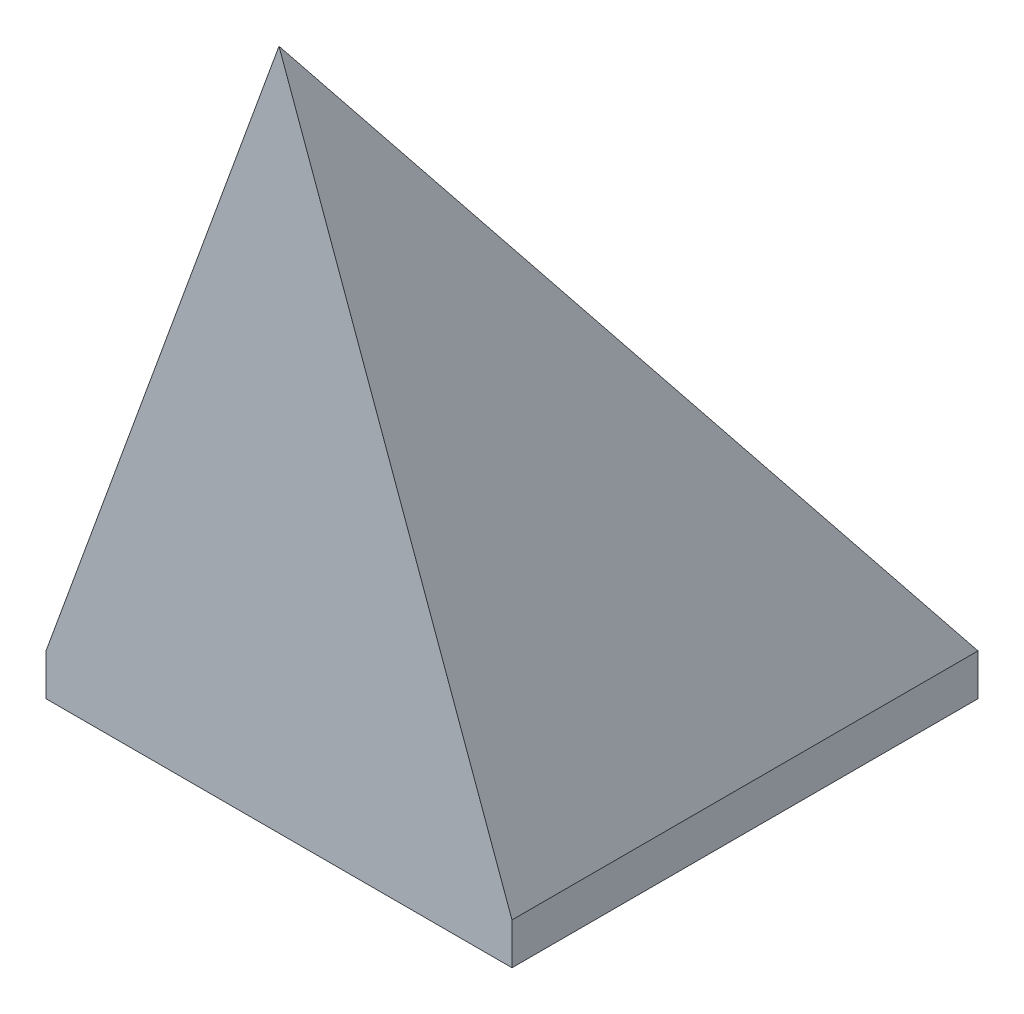
SolidWorks part; units mm, degrees
ref_plane "前视基准面" through (0, 0, 0) normal (0, 0, 1) x (1, 0, 0)
ref_plane "上视基准面" through (0, 0, 0) normal (0, 1, 0) x (1, 0, 0)
ref_plane "右视基准面" through (0, 0, 0) normal (1, 0, 0) x (0, 0, -1)
other "Configuration Table"
sketch "草图1" plane through (0, 0, 0) normal (0, 1, 0) x (1, 0, 0)
  line L1 (0, 0) -> (45, 0)
  line L2 (0, 0) -> (0, 45)
  line L3 (0, 45) -> (45, 45)
  line L4 (45, 0) -> (45, 45)
  circle A0 centre (15, 30) radius 1.7
  circle A1 centre (30, 30) radius 1.7
  circle A2 centre (15, 15) radius 1.7
  circle A3 centre (30, 15) radius 1.7
  point P15 (-39.4596, 30.7867)
  dimension "D3" = 3.4
  dimension "D4" = 3.4
  dimension "D5" = 3.4
  dimension "D6" = 3.4
  dimension "D1" = 45
  dimension "D2" = 45
  dimension "D7" = 15
  dimension "D8" = 15
  dimension "D9" = 15
  dimension "D10" = 15
  dimension "D11" = 15
  dimension "D12" = 15
  dimension "D13" = 15
  dimension "D14" = 15
extrude "凸台-拉伸1" add sketch "草图1" along normal blind 4
sketch "草图2" plane through (0, 0, 0) normal (0, 0, 1) x (1, 0, 0)
  line L0 (0, 4) -> (22.5, 65.8182)
  line L1 (22.5, 65.8182) -> (45, 4)
  line L2 (0, 4) -> (45, 4) construction
  line L3 (0, 4) -> (45, 4)
  dimension "D1" = 70
  dimension "D2" = 70
extrude "凸台-拉伸2" add sketch "草图2" against normal blind 5 contours L0 L1 L3
sketch "草图3" plane through (0, 4, 0) normal (0, 1, 0) x (1, 0, 0)
  line L0 (0, 5) -> (0, 45)
  line L1 (0, 45) -> (4, 45)
  line L2 (45, 45) -> (0, 45) construction
  line L3 (4, 45) -> (7, 5)
  line L4 (0, 5) -> (45, 5) construction
  line L5 (7, 5) -> (0, 5)
  dimension "D1" = 4
  dimension "D2" = 7
extrude "凸台-拉伸3" add sketch "草图3" along direction (0.342, 0.9397, 0) on the side of the normal up to vertex (61.8182 mm away)
sketch "草图4" plane through (0, 4, 0) normal (0, 1, 0) x (1, 0, 0)
  line L0 (45, 45) -> (41, 45)
  line L1 (45, 45) -> (4, 45) construction
  line L2 (41, 45) -> (38, 5)
  line L3 (7, 5) -> (45, 5) construction
  line L4 (38, 5) -> (45, 5)
  line L5 (45, 5) -> (45, 45)
  dimension "D1" = 4
  dimension "D2" = 7
extrude "凸台-拉伸4" add sketch "草图4" along direction (0.342, -0.9397, 0) on the side of the normal up to vertex (61.8182 mm away)
sketch "草图5" plane through (0, 0, 0) normal (0, 0, 1) x (1, 0, 0)
  line L0 (22.5, 65.8182) -> (19, 56.2021)
  line L1 (19, 56.2021) -> (11, 56.2021)
  line L2 (11, 56.2021) -> (11, 66.2021)
  line L3 (11, 66.2021) -> (34, 66.2021)
  line L4 (34, 66.2021) -> (34, 56.2021)
  line L5 (34, 56.2021) -> (26, 56.2021)
  line L6 (26, 56.2021) -> (22.5, 65.8182)
  dimension "D1" = 10
  dimension "D2" = 8
  dimension "D3" = 8
extrude "切除-拉伸1" cut sketch "草图5" against normal through all
sketch "草图6" plane through (41.0216, 14.9306, 0) normal (0.9397, 0.342, 0) x (0, 0, -1)
  line L0 (0, 54.1535) -> (45, -11.6321)
  line L1 (45, -11.6321) -> (45, 54.1535)
  line L2 (45, 54.1535) -> (0, 54.1535)
extrude "切除-拉伸2" cut sketch "草图6" along direction (1, 0, 0) on the side against the normal through all
sketch "草图8" plane through (34.3387, 12.4983, 2.5754) normal (-0.9374, -0.3412, -0.0703) x (-0.0661, -0.024, 0.9975)
  line L0 (-47.6934, -10.2641) -> (-46.0169, -7.7763)
  line L1 (-15.4397, 37.5964) -> (-47.6934, -10.2641) construction
  line L2 (-46.0169, -7.7763) -> (-42.6934, -10.1361)
  line L3 (-47.6934, -10.2641) -> (-7.5942, -9.238) construction
  line L4 (-42.6934, -10.1361) -> (-47.6934, -10.2641)
  dimension "D1" = 3
  dimension "D2" = 5
extrude "凸台-拉伸9" add sketch "草图8" along direction (-1, 0, 0) on the side of the normal up to surface (36.2519 mm away)
chamfer "倒角1" distance 5 angle 45 1 edges at (22.5, 4, -5)
sketch "草图10" plane through (34.3387, 12.4983, 2.5754) normal (-0.9374, -0.3412, -0.0703) x (-0.0661, -0.024, 0.9975)
  line L0 (-27.3587, 19.9101) -> (-30.7283, 14.9101)
  line L1 (-15.4397, 37.5964) -> (-46.0169, -7.7763) construction
  line L2 (-30.7283, 14.9101) -> (-7.5942, 14.9101)
  line L3 (-7.5942, 36.081) -> (-7.5942, -3.9171) construction
  line L4 (-7.5942, 14.9101) -> (-7.5942, 19.9101)
  line L5 (-7.5942, 19.9101) -> (-27.3587, 19.9101)
  dimension "D1" = 5
extrude "凸台-拉伸10" add sketch "草图10" along direction (-1, 0, 0) on the side of the normal up to surface (17.5384 mm away) contours L5 L0 L2 L4
sketch "草图13" plane through (0, 22.7969, -31.317) normal (0, 0.5885, -0.8085) x (-1, 0, 0)
  line L0 (-45, -23.2497) -> (0, -23.2497) construction
  line L1 (-25, -23.2497) -> (-20, -23.2497)
  line L2 (-25, -23.2497) -> (-25, 5.5055)
  line L3 (-25, 5.5055) -> (-20, 5.5055)
  line L4 (-20, -23.2497) -> (-20, 5.5055)
  line L5 (-13.7308, 5.5055) -> (-31.2692, 5.5055) construction
  line L6 (-22.5, 5.5055) -> (-22.5, -20.408) construction
  line L7 (-4.9616, -20.408) -> (-40.0384, -20.408) construction
  dimension "D1" = 5
extrude "凸台-拉伸11" add sketch "草图13" along direction (0, 0, -1) on the side against the normal up to surface (40 mm away)
